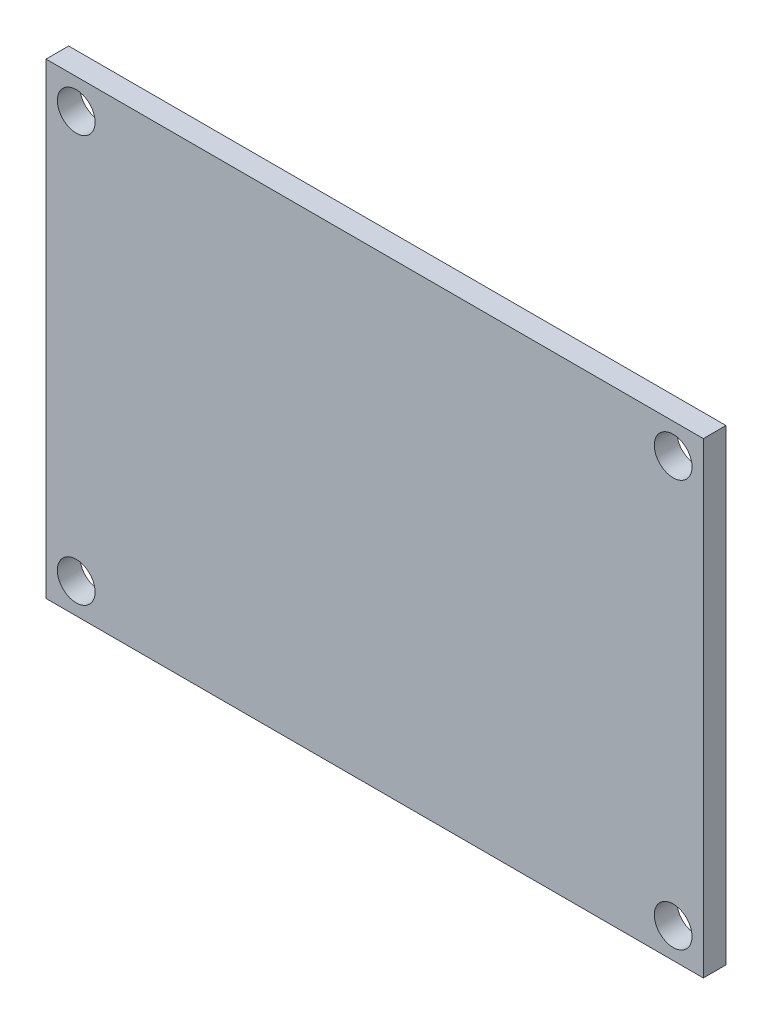
SolidWorks part; units mm, degrees
ref_plane "前视基准面" through (0, 0, 0) normal (0, 0, 1) x (1, 0, 0)
ref_plane "上视基准面" through (0, 0, 0) normal (0, 1, 0) x (1, 0, 0)
ref_plane "右视基准面" through (0, 0, 0) normal (1, 0, 0) x (0, 0, -1)
other "Configuration Table"
sketch "草图1" plane through (0, 0, 0) normal (0, 0, 1) x (1, 0, 0)
  line L1 (-43.55, 30.95) -> (43.55, 30.95)
  line L2 (-43.55, 30.95) -> (-43.55, -30.95)
  line L3 (-43.55, -30.95) -> (43.55, -30.95)
  line L4 (43.55, 30.95) -> (43.55, -30.95)
  point P4 (0, 30.95)
  point P5 (43.55, 0)
  dimension "D1" = 87.1
  dimension "D2" = 61.9
extrude "凸台-拉伸1" add sketch "草图1" along normal blind 3
sketch "草图2" plane through (0, 0, 0) normal (0, 0, -1) x (-1, 0, 0)
  line L0 (-43.55, -30.95) -> (-43.55, 30.95) construction
  line L1 (-43.55, 30.95) -> (43.55, 30.95) construction
  line L2 (43.55, -30.95) -> (-43.55, -30.95) construction
  line L3 (43.55, 30.95) -> (43.55, -30.95) construction
  circle A0 centre (-39.55, 26.95) radius 2.5
  circle A1 centre (-39.55, -26.95) radius 2.5
  circle A2 centre (39.55, -26.95) radius 2.5
  circle A3 centre (39.55, 26.95) radius 2.5
  dimension "D1" = 5
  dimension "D2" = 4
  dimension "D3" = 4
  dimension "D4" = 4
  dimension "D5" = 4
extrude "切除-拉伸1" cut sketch "草图2" against normal through all
